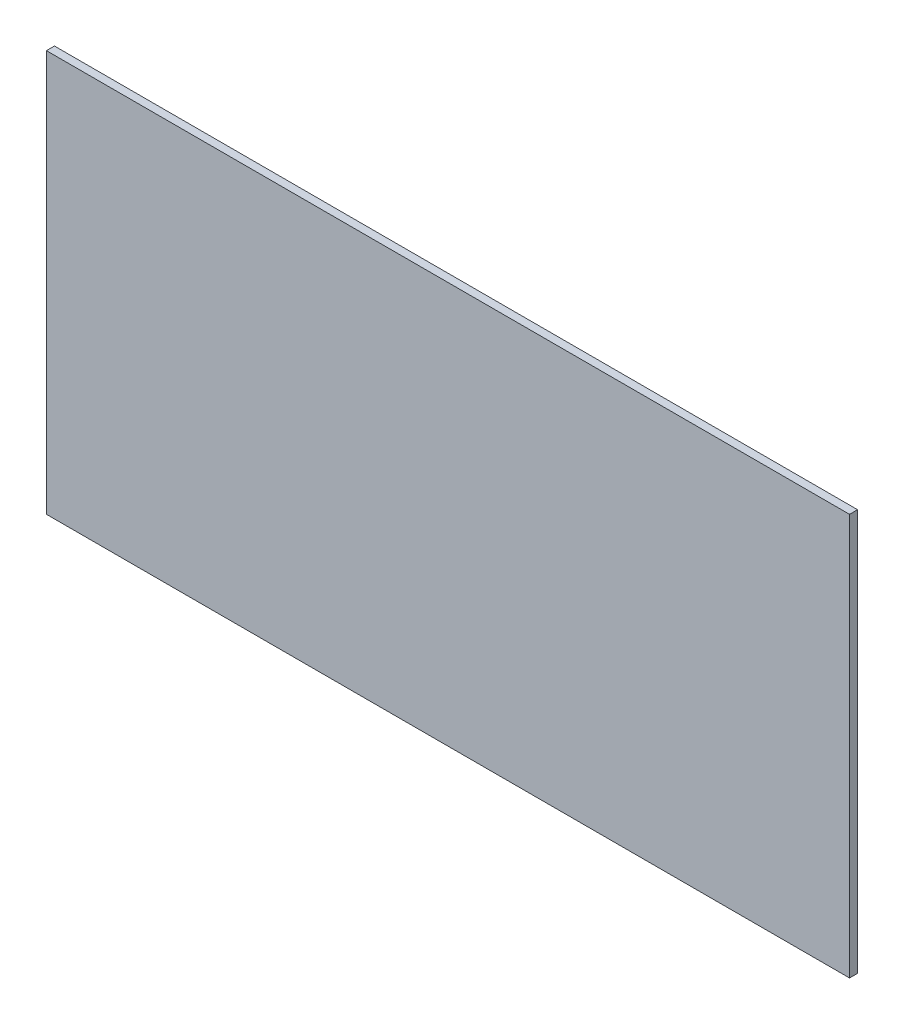
SolidWorks part; units mm, degrees
ref_plane "前视基准面" through (0, 0, 0) normal (0, 0, 1) x (1, 0, 0)
ref_plane "上视基准面" through (0, 0, 0) normal (0, 1, 0) x (1, 0, 0)
ref_plane "右视基准面" through (0, 0, 0) normal (1, 0, 0) x (0, 0, -1)
other "Configuration Table"
sketch "草图1" plane through (0, 0, 0) normal (0, 0, 1) x (1, 0, 0)
  line L1 (-1000, 500) -> (1000, 500)
  line L2 (-1000, 500) -> (-1000, -500)
  line L3 (-1000, -500) -> (1000, -500)
  line L4 (1000, 500) -> (1000, -500)
  line L5 (-1000, 500) -> (1000, -500) construction
  line L6 (-1000, -500) -> (1000, 500) construction
  point P0 (0, 0)
  dimension "D1" = 2000
  dimension "D2" = 1000
extrude "凸台-拉伸1" add sketch "草图1" along normal blind 20
